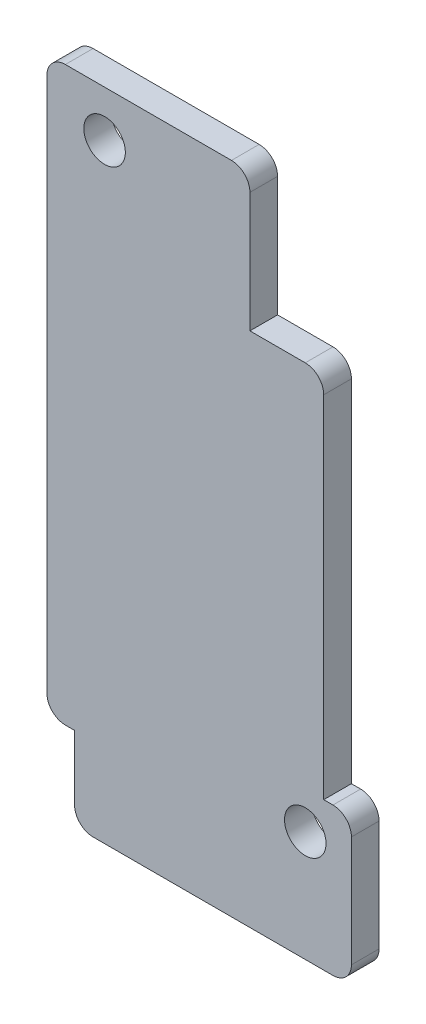
SolidWorks part; units mm, degrees
ref_plane "Front Plane" through (0, 0, 0) normal (0, 0, 1) x (1, 0, 0)
ref_plane "Top Plane" through (0, 0, 0) normal (0, 1, 0) x (1, 0, 0)
ref_plane "Right Plane" through (0, 0, 0) normal (1, 0, 0) x (0, 0, -1)
sketch "Sketch1" plane through (0, 0, 0) normal (0, 0, 1) x (1, 0, 0)
  line L1 (-14.0559, 16.0015) -> (15.9441, 16.0015)
  line L2 (-14.0559, 16.0015) -> (-14.0559, -54.9985)
  line L3 (-14.0559, -54.9985) -> (15.9441, -54.9985)
  line L4 (15.9441, 16.0015) -> (15.9441, -54.9985)
  dimension "D1" = 30
  dimension "D2" = 71
extrude "Boss-Extrude1" add sketch "Sketch1" along normal mid plane 3
sketch "Sketch3" plane through (0, 0, 1.5) normal (0, 0, 1) x (1, 0, 0)
  line L5 (15.9441, 16.0015) -> (7.9441, 16.0015)
  line L6 (15.9441, 16.0015) -> (15.9441, 1.0015)
  line L7 (15.9441, 1.0015) -> (7.9441, 1.0015)
  line L8 (7.9441, 16.0015) -> (7.9441, 1.0015)
  dimension "D1" = 15
  dimension "D2" = 8
extrude "Cut-Extrude1" cut sketch "Sketch3" against normal through all
sketch "Sketch6" plane through (15.9441, 0, 0) normal (1, 0, 0) x (0, 0, -1)
  line L0 (-1.5, -54.9985) -> (-1.5, 1.0015) construction
  line L1 (1.5, -54.9985) -> (-1.5, -54.9985)
  line L2 (1.5, -54.9985) -> (1.5, -38.9985)
  line L3 (1.5, -38.9985) -> (-1.5, -38.9985)
  line L4 (-1.5, -54.9985) -> (-1.5, -38.9985)
  dimension "D1" = 16
extrude "Boss-Extrude2" add sketch "Sketch6" along normal blind 3
hole_wizard "M4 Clearance Hole1" positions "Sketch4" profile "Sketch5" hole size "M4" standard "ANSI Metric" end condition through all
sketch "Sketch4" plane through (0, 0, -1.5) normal (0, 0, -1) x (-1, 0, 0)
  point P2 (7.8059, 11.0015)
  point P8 (-13.9441, -42.9985)
  point P14 (0, 0)
  point P15 (-13.9441, -42.9985)
sketch "Sketch5" plane through (-7.8059, 11.0015, -1.5) normal (1, 0, 0) x (0, 1, 0)
  line L0 (0, 0) -> (0, 3)
  line L1 (0, 3) -> (2.25, 3)
  line L2 (2.25, 3) -> (2.25, 0)
  line L5 (2.25, 0) -> (0, 0)
  line L11 (0, -6.35) -> (0, 107.95) construction
  dimension "Thru Hole Dia." = 4.5
  dimension "Thru Hole Depth" = 3
sketch "Sketch9" plane through (0, 0, -1.5) normal (0, 0, -1) x (-1, 0, 0)
  line L1 (14.0559, -54.9985) -> (11.0559, -54.9985)
  line L2 (14.0559, -54.9985) -> (14.0559, -45.9985)
  line L3 (14.0559, -45.9985) -> (11.0559, -45.9985)
  line L4 (11.0559, -54.9985) -> (11.0559, -45.9985)
  dimension "D1" = 3
  dimension "D2" = 9
extrude "Cut-Extrude2" cut sketch "Sketch9" against normal through all
fillet "Fillet1" radius 2 7 edges at (-14.0559, 16.0015, 0) (15.9441, 1.0015, 0) (7.9441, 16.0015, 0) (18.9441, -54.9985, 0) (18.9441, -38.9985, 0) (-11.0559, -54.9985, 0) (-14.0559, -45.9985, 0)
